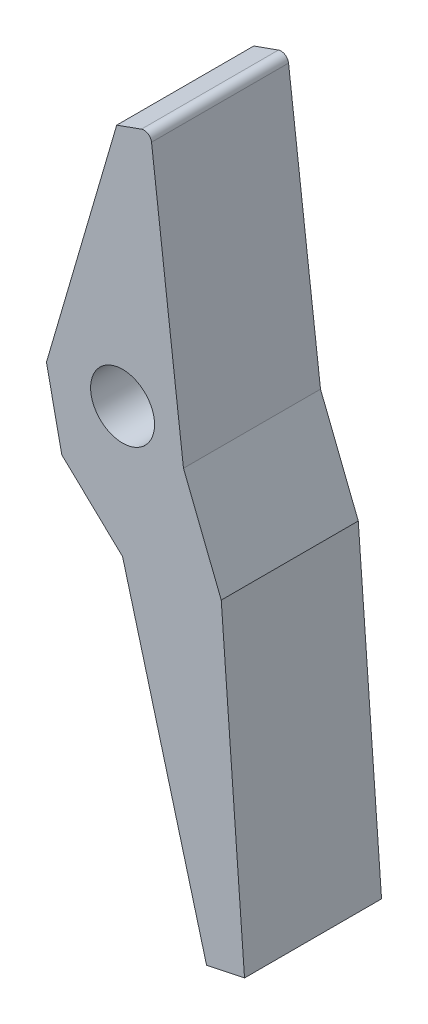
SolidWorks part; units mm, degrees
ref_plane "정면" through (0, 0, 0) normal (0, 0, 1) x (1, 0, 0)
ref_plane "윗면" through (0, 0, 0) normal (0, 1, 0) x (1, 0, 0)
ref_plane "우측면" through (0, 0, 0) normal (1, 0, 0) x (0, 0, -1)
sketch "스케치1" plane through (0, 0, 0) normal (0, 0, 1) x (1, 0, 0)
  line L0 (-5, 0) -> (-0.3852, 15.7953)
  line L1 (-0.3852, 15.7953) -> (1.8271, 16.5878)
  line L2 (1.8271, 16.5878) -> (4, -1.5319)
  line L3 (8.0096, -28.5205) -> (6.4798, -7.7898)
  line L4 (6.4798, -7.7898) -> (4, -1.5319)
  line L8 (-5, 0) -> (-3.993, -4.7619)
  line L9 (-3.993, -4.7619) -> (0, -8.5547)
  line L10 (0, -8.5547) -> (5.5177, -29.0475)
  line L11 (5.5177, -29.0475) -> (8.0096, -28.5205)
  circle A0 centre (0, 0) radius 2.1
  dimension "D1" = 4.2
  dimension "D2" = 2.35
  dimension "D3" = 15
  dimension "D4" = 9
  dimension "D5" = 5
  dimension "D6" = 15.8
extrude "보스-돌출1" add sketch "스케치1" along normal mid plane 9
sketch "스케치2" plane through (-4.6068, 1.3459, 0) normal (-0.9599, 0.2804, 0) x (0, 0, 1)
  circle A0 centre (0, 8) radius 2.4
  dimension "D1" = 4.8
  dimension "D2" = 8
extrude "보스-돌출2" add sketch "스케치2" along normal blind 2
fillet "필렛1" radius 1.75 1 edges at (-4.9561, 7.2821, 0)
sketch "스케치3" plane through (-4.6068, 1.3459, 0) normal (-0.9599, 0.2804, 0) x (0, 0, 1)
  circle A0 centre (0, 8) radius 2.4
  circle A1 centre (0, 8) radius 3.1
  dimension "D1" = 4.8
  dimension "D2" = 6.2
extrude "컷-돌출1" cut sketch "스케치3" against normal blind 2
fillet "필렛3" radius 0.5 1 edges at (1.8271, 16.5878, 0)
